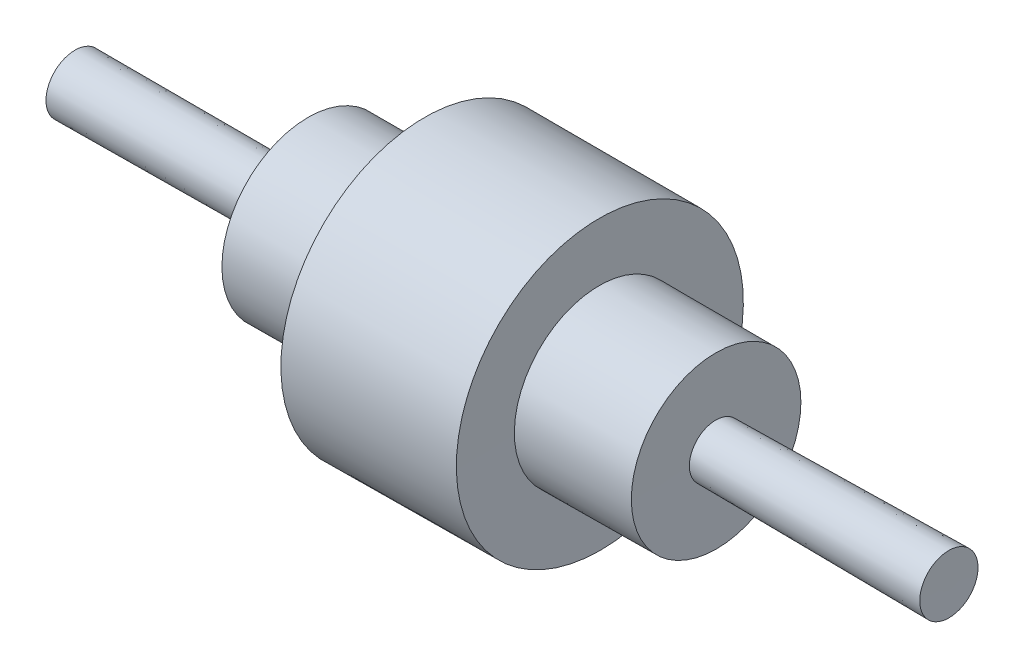
SolidWorks part; units mm, degrees
ref_plane "Ön Düzlem" through (0, 0, 0) normal (0, 0, 1) x (1, 0, 0)
ref_plane "Üst Düzlem" through (0, 0, 0) normal (0, 1, 0) x (1, 0, 0)
ref_plane "Sağ Düzlem" through (0, 0, 0) normal (1, 0, 0) x (0, 0, -1)
sketch "Sketch1" plane through (0, 0, 0) normal (0, 0, 1) x (1, 0, 0)
  line L4 (0, 0) -> (0, 10000)
  line L5 (0, 10000) -> (80000, 10000)
  line L6 (80000, 10000) -> (80000, 30000)
  line L7 (80000, 30000) -> (120000, 30000)
  line L8 (120000, 30000) -> (120000, 50000)
  line L9 (120000, 50000) -> (180000, 50000)
  line L10 (180000, 30000) -> (180000, 50000)
  line L11 (180000, 30000) -> (220000, 30000)
  line L12 (220000, 30000) -> (220000, 10000)
  line L13 (220000, 10000) -> (299990.7937, 11213.6408)
  line L14 (299990.7937, 11213.6408) -> (299990.7937, 1213.6408)
  line L15 (0, 0) -> (299990.7937, 1213.6408)
revolve "Revolve1" add sketch "Sketch1" angle 360 about L15
